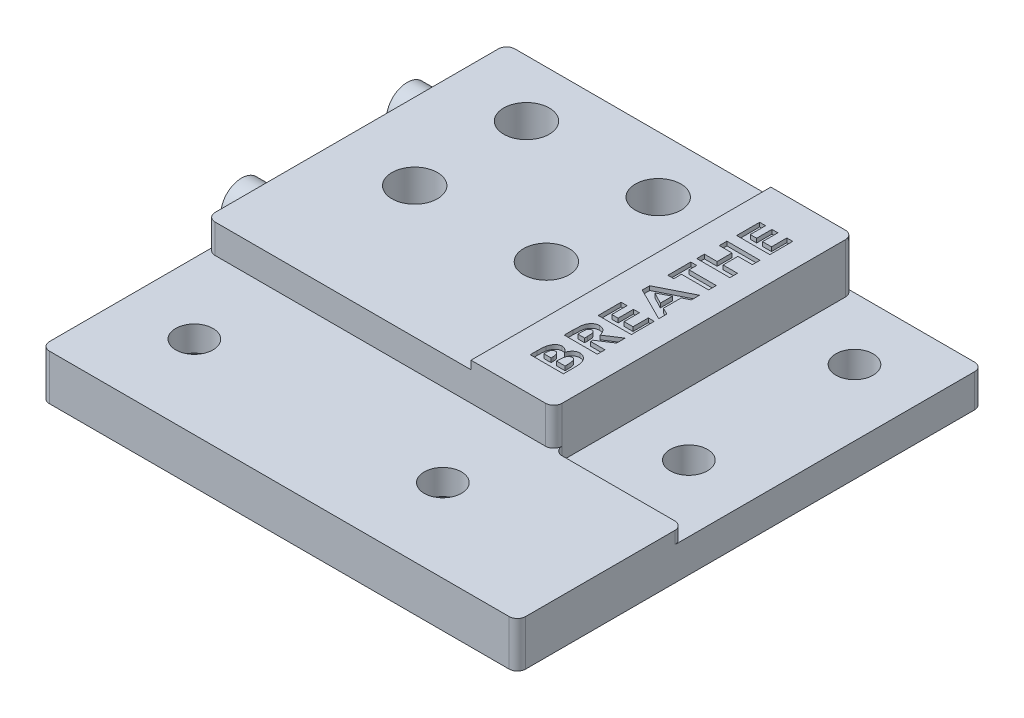
SolidWorks part; units mm, degrees
ref_plane "Front Plane" through (0, 0, 0) normal (0, 0, 1) x (1, 0, 0)
ref_plane "Top Plane" through (0, 0, 0) normal (0, 1, 0) x (1, 0, 0)
ref_plane "Right Plane" through (0, 0, 0) normal (1, 0, 0) x (0, 0, -1)
sketch "Sketch1" plane through (0, 0, 0) normal (0, 1, 0) x (1, 0, 0)
  line L0 (-19.25, 21.25) -> (-3.35, 7.75) construction
  line L1 (29, -28.1) -> (-29, -28.1)
  line L2 (29, -28.1) -> (29, 28.1)
  line L3 (29, 28.1) -> (-29, 28.1)
  line L4 (-29, -28.1) -> (-29, 28.1)
  line L5 (29, -28.1) -> (-29, 28.1) construction
  line L6 (29, 28.1) -> (-29, -28.1) construction
  line L7 (-19.25, 7.75) -> (-3.35, 7.75) construction
  line L8 (-19.25, 7.75) -> (-19.25, 21.25) construction
  line L9 (-19.25, 21.25) -> (-3.35, 21.25) construction
  line L10 (-3.35, 7.75) -> (-3.35, 21.25) construction
  line L11 (-11.3, 14.5) -> (-11.3, -18.1) construction
  line L13 (-24, 1.4) -> (1.4, 1.4) construction
  line L14 (-24, 1.4) -> (-24, 27.6) construction
  line L15 (-24, 27.6) -> (1.4, 27.6) construction
  line L16 (1.4, 1.4) -> (1.4, 27.6) construction
  line L17 (-24, 1.4) -> (1.4, 27.6) construction
  line L18 (-24, 27.6) -> (1.4, 1.4) construction
  point P0 (0, 0)
  point P10 (-11.3, 14.5)
  point P12 (-19.25, 21.25)
  point P13 (-3.35, 21.25)
  point P14 (-3.35, 7.75)
  point P15 (-19.25, 7.75)
  point P18 (-11.3, -18.1)
  dimension "D1" = 13.5
  dimension "D2" = 15.9
  dimension "D3" = 19.5
  dimension "D4" = 25.4
  dimension "D5" = 26.2
  dimension "D6" = 5
  dimension "D7" = 1
  dimension "D8" = 58
  dimension "D9" = 10
extrude "Boss-Extrude1" add sketch "Sketch1" along normal blind 9
hole_wizard "Ø4.0mm Dowel Hole1" positions "3DSketch1" profile "Sketch2" hole size "Ø4.0" standard "ANSI Metric" end condition through all
sketch3d "3DSketch1"
  point P0 (-3.35, 0, -7.75)
  point P2 (-19.25, 0, -7.75)
  point P5 (-19.25, 0, -21.25)
  point P8 (-3.35, 0, -21.25)
  point P13 (-19.25, 0, -7.75)
  point P15 (-19.25, 0, -21.25)
  point P17 (-3.35, 0, -21.25)
sketch "Sketch2" plane through (-3.35, 0, -7.75) normal (1, 0, 0) x (0, 0, -1)
  line L0 (0, 0) -> (0, 9)
  line L1 (0, 9) -> (2, 9)
  line L2 (2, 9) -> (2, 0)
  line L5 (2, 0) -> (0, 0)
  line L11 (0, -6.35) -> (0, 107.95) construction
  dimension "Thru Hole Dia." = 4
  dimension "Thru Hole Depth" = 9
ref_plane "Plane1" through (-11.3, 0, 0) normal (1, 0, 0) x (0, 0, -1)
ref_plane "Plane2" through (0, 0, -14.5) normal (0, 0, 1) x (1, 0, 0)
sketch "Sketch12" plane through (0, 0, 0) normal (0, 1, 0) x (1, 0, 0)
  point P0 (10, -18.1004)
  point P2 (-20, -18.1004)
hole_wizard "CSK for M4 Flat Head Machine Screw1" positions "3DSketch2" profile "Sketch5" countersink size "M4" standard "ANSI Metric" end condition through all
sketch3d "3DSketch2"
  point P8 (-20, 0, 18.1004)
  point P11 (10, 0, 18.1004)
sketch "Sketch5" plane through (-20, 0, 18.1004) normal (1, 0, 0) x (0, 0, -1)
  line L0 (0, 0) -> (0, 9)
  line L1 (0, 9) -> (2.25, 9)
  line L2 (2.25, 9) -> (2.25, 2.45)
  line L3 (2.25, 2.45) -> (4.7, 0)
  line L5 (4.7, 0) -> (0, 0)
  line L6 (-2.25, 2.45) -> (-4.7, 0) construction
  line L11 (0, -6.35) -> (0, 107.95) construction
  dimension "Thru Hole Dia." = 4.5
  dimension "Thru Hole Depth" = 9
  dimension "Near C'Sink Dia." = 9.4
  dimension "Near C'Sink Angle" = 90
sketch "Sketch6" plane through (0, 0, 0) normal (0, -1, 0) x (1, 0, 0)
  circle A0 centre (-19.25, -21.25) radius 2.75
  circle A1 centre (-19.25, -7.75) radius 2.75
  circle A2 centre (-3.35, -21.25) radius 2.75
  circle A3 centre (-3.35, -7.75) radius 2.75
  dimension "D1" = 5.5
extrude "Cut-Extrude1" cut sketch "Sketch6" against normal blind 9
sketch "Sketch7" plane through (0, 0, 0) normal (0, -1, 0) x (1, 0, 0)
  circle A0 centre (-19.25, -21.25) radius 4
  circle A1 centre (-19.25, -7.75) radius 4
  circle A2 centre (-3.35, -21.25) radius 4
  circle A3 centre (-3.35, -7.75) radius 4
  dimension "D1" = 8
extrude "Cut-Extrude2" cut sketch "Sketch7" against normal blind 1.5
sketch "Sketch8" plane through (0, 9, 0) normal (0, 1, 0) x (1, 0, 0)
  line L0 (29, -28.1) -> (29, 28.1) construction
  line L1 (-29, -28.1) -> (29, -28.1)
  line L2 (-29, -28.1) -> (-29, -8.1)
  line L3 (-29, -8.1) -> (29, -8.1)
  line L4 (29, -28.1) -> (29, -8.1)
  dimension "D1" = 20
extrude "Cut-Extrude3" cut sketch "Sketch8" against normal blind 3.5
sketch "Sketch9" plane through (0, 9, 0) normal (0, 1, 0) x (1, 0, 0)
  line L0 (29, -8.1) -> (-29, -8.1) construction
  line L1 (29, 28.1) -> (13.4, 28.1)
  line L2 (29, 28.1) -> (29, -8.1)
  line L3 (29, -8.1) -> (13.4, -8.1)
  line L4 (13.4, 28.1) -> (13.4, -8.1)
  line L6 (-21.5, 0.9) -> (5.9, 0.9) construction
  dimension "D2" = 9
extrude "Cut-Extrude4" cut sketch "Sketch9" against normal offset from surface (5 mm away) 4 up to face at (-19.25, 0, -11.75)
sketch "Sketch10" plane through (0, 4, 0) normal (0, 1, 0) x (1, 0, 0)
  line L0 (21, 28.1) -> (21, -8.1) construction
  line L4 (-29, 28.1) -> (-29, -8.1) construction
  point P6 (21, 0.6)
  point P7 (21, 20.6)
  dimension "D1" = 20
  dimension "D2" = 7.5
  dimension "D3" = 50
hole_wizard "M4 Clearance Hole1" positions "3DSketch3" profile "Sketch11" hole size "M4" standard "BSI" end condition through all
sketch3d "3DSketch3"
  point P0 (21, 4, -20.6)
  point P3 (21, 4, -0.6)
sketch "Sketch11" plane through (21, 4, -20.6) normal (1, 0, 0) x (0, 0, 1)
  line L0 (0, 0) -> (0, 4)
  line L1 (0, 4) -> (2.25, 4)
  line L2 (2.25, 4) -> (2.25, 0)
  line L5 (2.25, 0) -> (0, 0)
  line L11 (0, -6.35) -> (0, 107.95) construction
  dimension "Thru Hole Dia." = 4.5
  dimension "Thru Hole Depth" = 4
sketch "Sketch14" plane through (0, 0, 0) normal (0, -1, 0) x (1, 0, 0)
  line L0 (-29, 28.1) -> (29, 28.1) construction
  line L1 (-29, -28.1) -> (-28.5, -28.1)
  line L2 (-29, -28.1) -> (-29, 28.1)
  line L3 (-29, 28.1) -> (-28.5, 28.1)
  line L4 (-28.5, -28.1) -> (-28.5, 28.1)
  dimension "D1" = 0.5
extrude "Cut-Extrude6" cut sketch "Sketch14" against normal through all
sketch "Sketch16" plane through (0, 9, 0) normal (0, 1, 0) x (1, 0, 0)
  line L0 (13.4, 28.1) -> (-28.5, 28.1) construction
  line L1 (13.4, -8.1) -> (3.4, -8.1)
  line L2 (13.4, -8.1) -> (13.4, 28.1)
  line L3 (13.4, 28.1) -> (3.4, 28.1)
  line L4 (3.4, -8.1) -> (3.4, 28.1)
  dimension "D1" = 10
extrude "Boss-Extrude3" add sketch "Sketch16" along normal blind 1
fillet "Fillet4" radius 1 8 edges at (29, 2.75, 28.1) (13.4, 4.75, 8.1) (29, 4.75, 8.1) (29, 2, -28.1) (13.4, 7, -28.1) (-28.5, 7.25, 8.1) (-28.5, 2.75, 28.1) (-28.5, 4.5, -28.1)
fillet "Fillet5" radius 1 1 edges at (13.4, 7.75, 8.1)
sketch "Sketch15" plane through (-28.5, 0, 0) normal (-1, 0, 0) x (0, 0, 1)
  line L0 (-28.1, 4.5) -> (28.1, 4.5) construction
  line L1 (-28.1, 0) -> (-28.1, 9) construction
  line L2 (28.1, 5.5) -> (28.1, 0) construction
  circle A0 centre (-20.1, 4.5) radius 2.5
  circle A1 centre (-0.1, 4.5) radius 2.5
  dimension "D1" = 5
  dimension "D2" = 8
  dimension "D3" = 20
extrude "Boss-Extrude2" add sketch "Sketch15" along normal blind 4
sketch "Sketch13" plane through (0, 10, 0) normal (0, 1, 0) x (1, 0, 0)
  line L0 (10.4, -6.1) -> (10.4, 26.1) construction
  line L1 (13.4, 27.1) -> (13.4, -7.1) construction
  line L2 (3.4, 28.1) -> (-27.5, 28.1) construction
  line L3 (12.4, -8.1) -> (-27.5, -8.1) construction
  text T0 "<b>BREATHE</b>" font "Century Gothic" height 4
  dimension "D1" = 3
  dimension "D2" = 2
  dimension "D3" = 2
extrude "Cut-Extrude5" cut sketch "Sketch13" against normal blind 0.5
